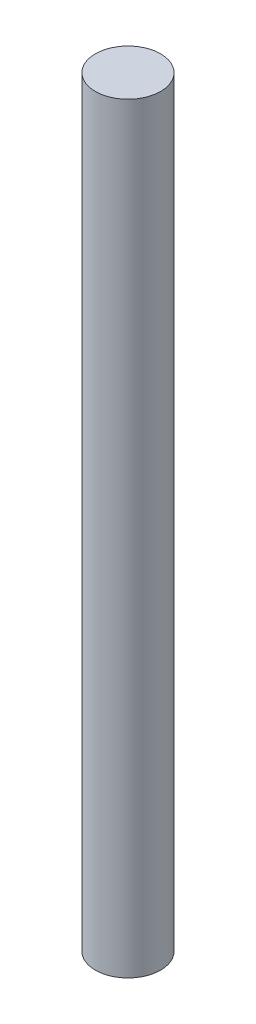
SolidWorks part; units mm, degrees
ref_plane "Front Plane" through (0, 0, 0) normal (0, 0, 1) x (1, 0, 0)
ref_plane "Top Plane" through (0, 0, 0) normal (0, 1, 0) x (1, 0, 0)
ref_plane "Right Plane" through (0, 0, 0) normal (1, 0, 0) x (0, 0, -1)
sketch "Sketch1" plane through (0, 0, 0) normal (0, 1, 0) x (1, 0, 0)
  circle A0 centre (0, 0) radius 1.905
  dimension "D1" = 3.81
extrude "Boss-Extrude1" add sketch "Sketch1" along normal blind 44.45
